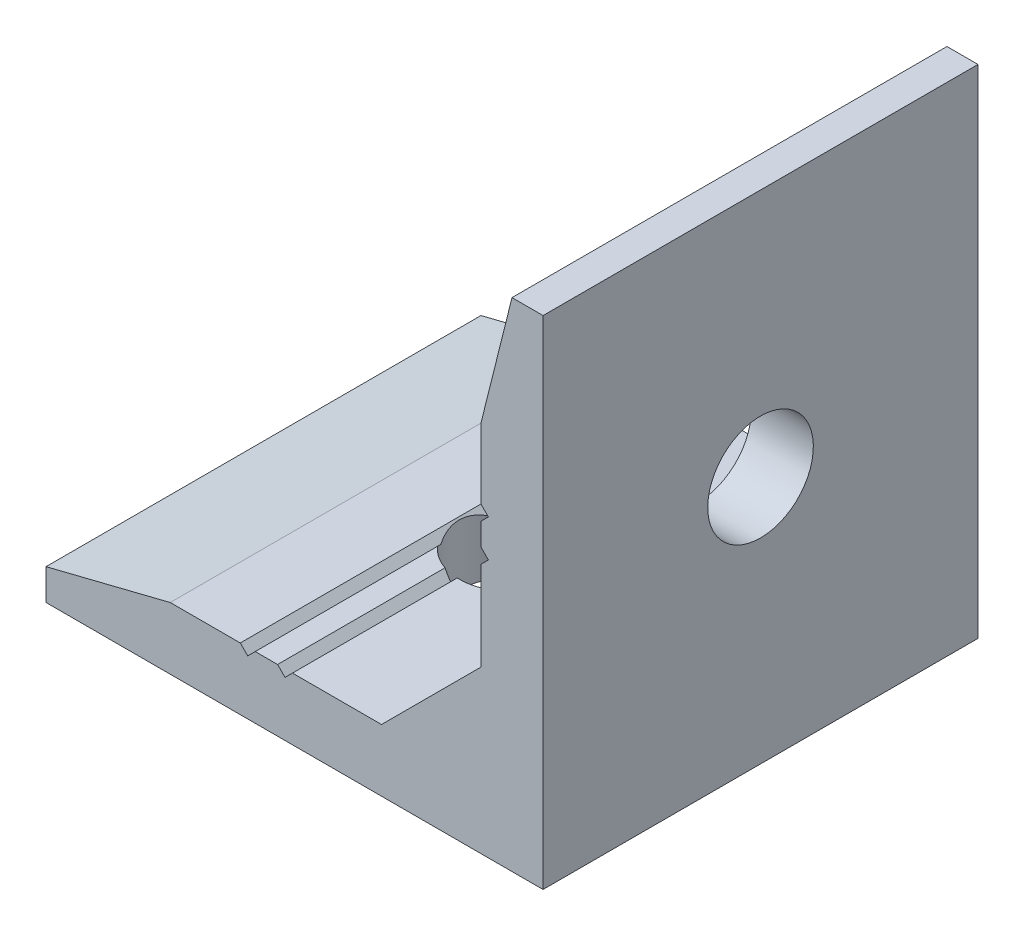
SolidWorks part; units mm, degrees
ref_plane "前视基准面" through (0, 0, 0) normal (0, 0, 1) x (1, 0, 0)
ref_plane "上视基准面" through (0, 0, 0) normal (0, 1, 0) x (1, 0, 0)
ref_plane "右视基准面" through (0, 0, 0) normal (1, 0, 0) x (0, 0, -1)
sketch "草图1" plane through (0, 0, 0) normal (0, 0, 1) x (1, 0, 0)
  line B0 (0, 0) -> (40, 0)
  line B1 (40, 0) -> (40, 40)
  line B2 (10, 5) -> (15.635, 5)
  line B3 (16.835, 5) -> (18.635, 5)
  line B4 (19.835, 5) -> (27, 5)
  line B5 (35, 13) -> (35, 20.165)
  line B6 (35, 21.365) -> (35, 23.165)
  line B7 (35, 24.365) -> (35, 30)
  line B8 (0, 2.5) -> (0, 0)
  line B9 (37.5, 40) -> (40, 40)
  line B10 (0, 2.5) -> (10, 5)
  line B11 (37.5, 40) -> (35, 30)
  line B12 (27, 5) -> (35, 13)
  line B13 (16.235, 4.4) -> (15.635, 5)
  line B14 (16.235, 4.4) -> (16.835, 5)
  line B15 (19.235, 4.4) -> (18.635, 5)
  line B16 (19.235, 4.4) -> (19.835, 5)
  line B17 (35.6, 23.765) -> (35, 24.365)
  line B18 (35.6, 23.765) -> (35, 23.165)
  line B19 (35.6, 20.765) -> (35, 21.365)
  line B20 (35.6, 20.765) -> (35, 20.165)
sketch_block_instance "A$C2EE5613F-1"
sketch_block "A$C2EE5613F"
extrude "凸台-拉伸1" add sketch "草图1" along normal mid plane 35
sketch "草图3" plane through (0, 5, 0) normal (0, 1, 0) x (1, 0, 0)
  line L0 (0, -17.5) -> (0, 17.5) construction
  circle A0 centre (20, 0) radius 4.25
  dimension "D1" = 20
extrude "切除-拉伸1" cut sketch "草图3" against normal through all
sketch "草图4" plane through (35, 0, 0) normal (-1, 0, 0) x (0, 0, 1)
  line L0 (17.5, 40) -> (-17.5, 40) construction
  circle A0 centre (0, 20) radius 4.25
  dimension "D1" = 20
extrude "切除-拉伸2" cut sketch "草图4" against normal through all
